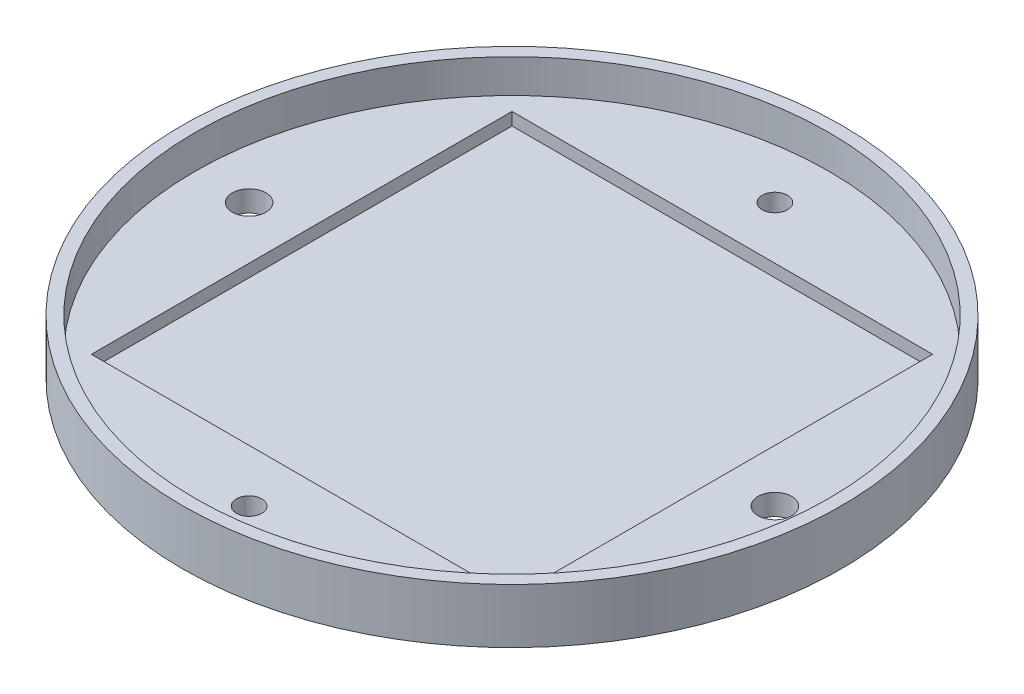
SolidWorks part; units mm, degrees
material "Custom Plastic"
ref_plane "Front Plane" through (0, 0, 0) normal (0, 0, 1) x (1, 0, 0)
ref_plane "Top Plane" through (0, 0, 0) normal (0, 1, 0) x (1, 0, 0)
ref_plane "Right Plane" through (0, 0, 0) normal (1, 0, 0) x (0, 0, -1)
sketch "Sketch1" plane through (0, 0, 0) normal (0, 1, 0) x (1, 0, 0)
  circle A0 centre (0, 0) radius 78.35
  circle A1 centre (0, 0) radius 62.5 construction
  circle A2 centre (-62.5, 0) radius 4
  circle A3 centre (62.5, 0) radius 4
  circle A4 centre (0, 62.5) radius 3
  circle A5 centre (0, -62.5) radius 3
  dimension "D1" = 156.7
  dimension "D2" = 125
  dimension "D3" = 8
  dimension "D4" = 8
  dimension "D5" = 6
  dimension "D6" = 6
extrude "Boss-Extrude1" add sketch "Sketch1" along normal blind 5
sketch "Sketch2" plane through (0, 5, 0) normal (0, 1, 0) x (1, 0, 0)
  circle A0 centre (0, 0) radius 75.35
  circle A1 centre (0, 0) radius 78.35
  circle A2 centre (0, 0) radius 78.35
  dimension "D1" = 0
  dimension "D2" = 3
extrude "Boss-Extrude2" add sketch "Sketch2" along normal blind 8
sketch "Sketch3" plane through (0, 5, 0) normal (0, 1, 0) x (1, 0, 0)
  line L1 (-50, -50) -> (50, -50)
  line L2 (-50, -50) -> (-50, 50)
  line L3 (-50, 50) -> (50, 50)
  line L4 (50, -50) -> (50, 50)
  line L5 (-50, -50) -> (50, 50) construction
  line L6 (-50, 50) -> (50, -50) construction
  point P0 (0, 0)
  dimension "D1" = 100
  dimension "D2" = 100
extrude "Cut-Extrude1" cut sketch "Sketch3" against normal blind 3
